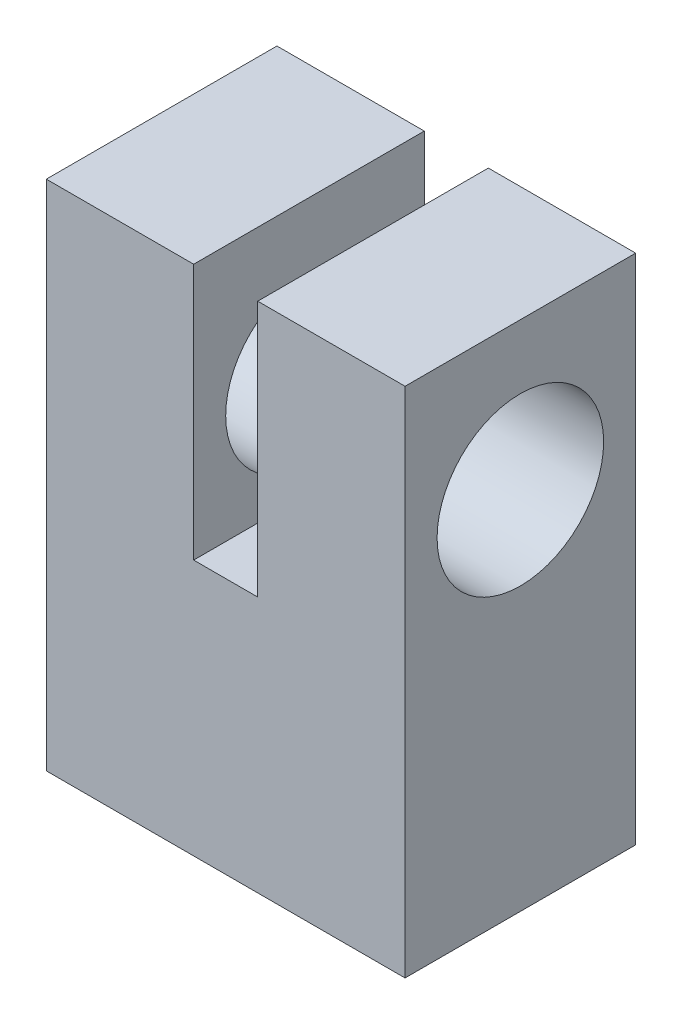
SolidWorks part; units mm, degrees
ref_plane "前视基准面" through (0, 0, 0) normal (0, 0, 1) x (1, 0, 0)
ref_plane "上视基准面" through (0, 0, 0) normal (0, 1, 0) x (1, 0, 0)
ref_plane "右视基准面" through (0, 0, 0) normal (1, 0, 0) x (0, 0, -1)
sketch "草图1" plane through (0, 0, 0) normal (0, 1, 0) x (1, 0, 0)
  line L0 (0, 0) -> (28, 0)
  line L1 (28, 0) -> (28, 18)
  line L2 (28, 18) -> (0, 18)
  line L3 (0, 18) -> (0, 0)
  dimension "D1" = 18
  dimension "D2" = 28
extrude "凸台-拉伸1" add sketch "草图1" along normal blind 40
sketch "草图2" plane through (0, 0, 0) normal (0, -1, 0) x (1, 0, 0)
  line L0 (0, -18) -> (0, 0) construction
  line L1 (0, 0) -> (28, 0) construction
  line L2 (28, -18) -> (0, -18) construction
  line L3 (14, 0) -> (14, 1.7025) construction
  circle A0 centre (6, -5.5) radius 2
  circle A1 centre (6, -12.5) radius 2
  circle A2 centre (22, -12.5) radius 2
  circle A3 centre (22, -5.5) radius 2
  dimension "D1" = 6
  dimension "D3" = 6
  dimension "D2" = 5.5
  dimension "D4" = 5.5
extrude "切除-拉伸1" cut sketch "草图2" against normal blind 15
sketch "草图4" plane through (28, 0, 0) normal (1, 0, 0) x (0, 0, -1)
  line L0 (0, 0) -> (18, 0) construction
  circle A0 centre (9, 28.5) radius 7.5
  dimension "D1" = 28.5
extrude "切除-拉伸2" cut sketch "草图4" against normal blind 1.2
sketch "草图5" plane through (26.8, 0, 0) normal (1, 0, 0) x (0, 0, -1)
  circle A0 centre (9, 28.5) radius 6.5
extrude "切除-拉伸3" cut sketch "草图5" against normal blind 3.2
sketch "草图6" plane through (23.6, 0, 0) normal (1, 0, 0) x (0, 0, -1)
  circle A0 centre (9, 28.5) radius 2.5
extrude "切除-拉伸4" cut sketch "草图6" against normal up to next
sketch "草图7" plane through (0, 0, 0) normal (-1, 0, 0) x (0, 0, 1)
  circle A0 centre (-9, 28.5) radius 7.5
extrude "切除-拉伸5" cut sketch "草图7" against normal blind 1.2
sketch "草图8" plane through (1.2, 0, 0) normal (-1, 0, 0) x (0, 0, 1)
  circle A0 centre (-9, 28.5) radius 6.5
extrude "切除-拉伸6" cut sketch "草图8" against normal blind 3.2
sketch "草图9" plane through (0, 0, 0) normal (0, 0, 1) x (1, 0, 0)
  line L0 (14, 40) -> (11.5, 40)
  line L1 (0, 40) -> (28, 40) construction
  line L2 (11.5, 40) -> (11.5, 20)
  line L3 (11.5, 20) -> (16.5, 20)
  line L4 (16.5, 20) -> (16.5, 40)
  line L5 (16.5, 40) -> (14, 40)
  dimension "D1" = 2.5
  dimension "D2" = 2.5
  dimension "D3" = 20
extrude "切除-拉伸7" cut sketch "草图9" against normal through all
sketch "草图10" plane through (26.8, 0, 0) normal (1, 0, 0) x (0, 0, -1)
  circle A0 centre (9, 28.5) radius 6.5 construction
  circle A1 centre (9, 28.5) radius 7.5
  circle A2 centre (9, 28.5) radius 7.5
  circle A3 centre (9, 28.5) radius 6.5
  dimension "D1" = 0
extrude "凸台-拉伸2" add sketch "草图10" along normal blind 1.2
sketch "草图11" plane through (1.2, 0, 0) normal (-1, 0, 0) x (0, 0, 1)
  circle A0 centre (-9, 28.5) radius 6.5 construction
  circle A1 centre (-9, 28.5) radius 7.5
  circle A2 centre (-9, 28.5) radius 7.5
  circle A3 centre (-9, 28.5) radius 6.5
  dimension "D1" = 0
extrude "凸台-拉伸3" add sketch "草图11" along normal blind 1.2
sketch "草图12" plane through (4.4, 0, 0) normal (-1, 0, 0) x (0, 0, 1)
  circle A1 centre (-9, 28.5) radius 6.5
  circle A2 centre (-9, 28.5) radius 6.5
  dimension "D1" = 0
extrude "切除-拉伸8" cut sketch "草图12" against normal up to surface (19.2 mm away) up to face at (23.6, 28.5, -11.5)
